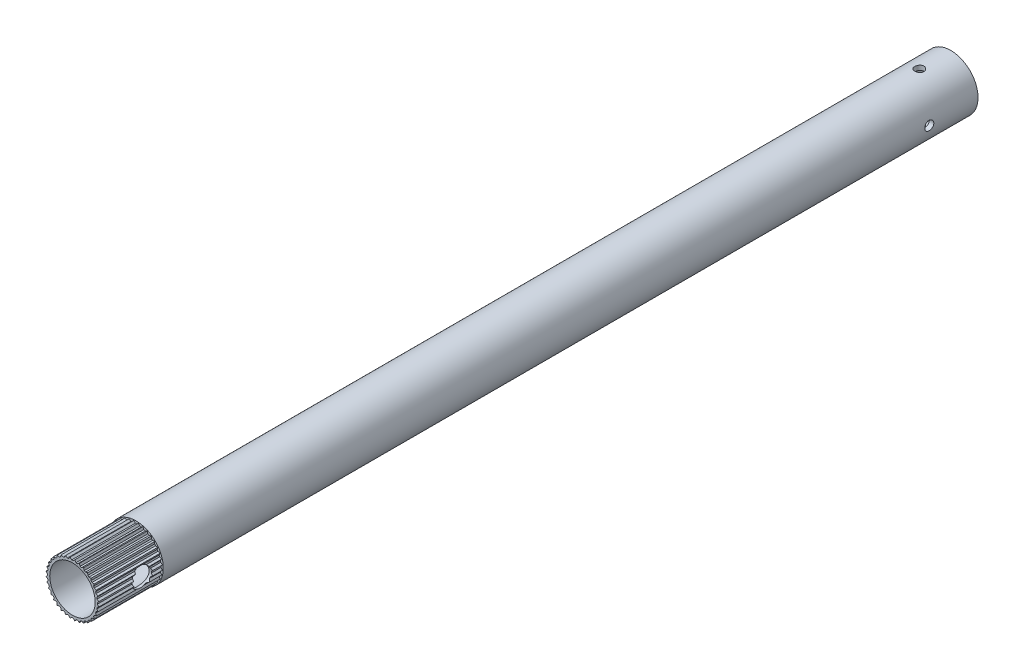
SolidWorks part; units mm, degrees
material "AISI 4130 Steel, normalized at 870C"
ref_plane "X-Y Datum" through (0, 0, 0) normal (0, 0, 1) x (1, 0, 0)
ref_plane "X-Z Datum" through (0, 0, 0) normal (0, 1, 0) x (1, 0, 0)
ref_plane "Y-Z Datum" through (0, 0, 0) normal (1, 0, 0) x (0, 0, -1)
sketch "Sketch1" plane through (0, 0, 0) normal (0, 1, 0) x (1, 0, 0)
  line L0 (9.5377, -364.395) -> (9.5377, -22.1596)
  line L1 (9.5377, -22.1596) -> (7.9375, -22.1596)
  line L2 (7.9375, -22.1596) -> (7.9375, -364.395)
  line L3 (7.9375, -364.395) -> (9.5377, -364.395)
  line L4 (0, -10.4775) -> (0, 10.4775) construction
  line L7 (0, -429.9496) -> (0, 0.9948) construction
revolve "Revolve1" [suppressed] add sketch "Sketch1" angle 360 about L7
sketch "Sketch2" plane through (0, 0, 0) normal (0, 1, 0) x (1, 0, 0)
  circle A0 centre (0, -33.1635) radius 1.5875 construction
  circle A4 centre (0, -33.1635) radius 1.5875
  circle A5 centre (0, -371.1514) radius 3.3782
  circle A6 centre (0, -371.1514) radius 3.3782 construction
extrude "Cut-Extrude2" [suppressed] cut sketch "Sketch2" against normal through all both and the other way through all
sketch "Sketch3" plane through (0, 0, 0) normal (1, 0, 0) x (0, 0, -1)
  circle A1 centre (-39.196, 0) radius 1.5875
  circle A2 centre (-39.196, 0) radius 1.5875 construction
extrude "Cut-Extrude3" [suppressed] cut sketch "Sketch3" against normal through all both and the other way through all
sketch "Sketch5" plane through (0, 0, 0) normal (0, 1, 0) x (1, 0, 0)
  line L0 (7.9375, -329.0759) -> (7.9375, -22.1596)
  line L1 (7.9375, -22.1596) -> (9.525, -22.1596)
  line L2 (9.525, -22.1596) -> (9.525, -329.0759)
  line L3 (9.525, -329.0759) -> (7.9375, -329.0759)
  line L4 (0, 0) -> (0, -348.3259) construction
  line L10 (0, 2.0157) -> (0, -439.4327) construction
revolve "Revolve2" add sketch "Sketch5" angle 360 about L10
sketch "Sketch6" plane through (0, 0, 0) normal (0, 1, 0) x (1, 0, 0)
  circle A0 centre (0, -33.1635) radius 1.5875 construction
  circle A1 centre (0, -33.1635) radius 1.5875
sketch "Sketch7" plane through (0, 0, 0) normal (1, 0, 0) x (0, 0, -1)
  circle A0 centre (-313.5823, 0) radius 3.3782 construction
  circle A2 centre (-39.196, 0) radius 1.5875
  circle A3 centre (-313.5823, 0) radius 3.3782
  circle A4 centre (-39.196, 0) radius 1.5875 construction
extrude "Cut-Extrude5" cut sketch "Sketch7" against normal through all both and the other way through all
extrude "Cut-Extrude6" cut sketch "Sketch6" against normal through all both and the other way through all
sketch "Sketch8" plane through (0, 0, 0) normal (0, 0, 1) x (1, 0, 0)
  line L0 (9.2357, -0.808) -> (8.6817, -0.254)
  line L1 (8.6817, -0.254) -> (8.6817, 0.254)
  line L2 (8.6817, 0.254) -> (9.2357, 0.808)
  line L3 (8.6817, 0) -> (0, 0) construction
  line L4 (8.9551, -2.3995) -> (8.5057, -1.7577)
  line L5 (8.5057, -1.7577) -> (8.5939, -1.2574)
  line L6 (8.5939, -1.2574) -> (9.2357, -0.808)
  line L7 (8.4024, -3.9181) -> (8.0713, -3.208)
  line L8 (8.0713, -3.208) -> (8.245, -2.7306)
  line L9 (8.245, -2.7306) -> (8.9551, -2.3995)
  line L10 (7.5944, -5.3176) -> (7.3916, -4.5608)
  line L11 (7.3916, -4.5608) -> (7.6456, -4.1209)
  line L12 (7.6456, -4.1209) -> (8.4024, -3.9181)
  line L13 (6.5556, -6.5556) -> (6.4873, -5.7751)
  line L14 (6.4873, -5.7751) -> (6.8138, -5.3859)
  line L15 (6.8138, -5.3859) -> (7.5944, -5.3176)
  line L16 (5.3176, -7.5944) -> (5.3859, -6.8138)
  line L17 (5.3859, -6.8138) -> (5.7751, -6.4873)
  line L18 (5.7751, -6.4873) -> (6.5556, -6.5556)
  line L19 (3.9181, -8.4024) -> (4.1209, -7.6456)
  line L20 (4.1209, -7.6456) -> (4.5608, -7.3916)
  line L21 (4.5608, -7.3916) -> (5.3176, -7.5944)
  line L22 (2.3995, -8.9551) -> (2.7306, -8.245)
  line L23 (2.7306, -8.245) -> (3.208, -8.0713)
  line L24 (3.208, -8.0713) -> (3.9181, -8.4024)
  line L25 (0.808, -9.2357) -> (1.2574, -8.5939)
  line L26 (1.2574, -8.5939) -> (1.7577, -8.5057)
  line L27 (1.7577, -8.5057) -> (2.3995, -8.9551)
  line L28 (-0.808, -9.2357) -> (-0.254, -8.6817)
  line L29 (-0.254, -8.6817) -> (0.254, -8.6817)
  line L30 (0.254, -8.6817) -> (0.808, -9.2357)
  line L31 (-2.3995, -8.9551) -> (-1.7577, -8.5057)
  line L32 (-1.7577, -8.5057) -> (-1.2574, -8.5939)
  line L33 (-1.2574, -8.5939) -> (-0.808, -9.2357)
  line L34 (-3.9181, -8.4024) -> (-3.208, -8.0713)
  line L35 (-3.208, -8.0713) -> (-2.7306, -8.245)
  line L36 (-2.7306, -8.245) -> (-2.3995, -8.9551)
  line L37 (-5.3176, -7.5944) -> (-4.5608, -7.3916)
  line L38 (-4.5608, -7.3916) -> (-4.1209, -7.6456)
  line L39 (-4.1209, -7.6456) -> (-3.9181, -8.4024)
  line L40 (-6.5556, -6.5556) -> (-5.7751, -6.4873)
  line L41 (-5.7751, -6.4873) -> (-5.3859, -6.8138)
  line L42 (-5.3859, -6.8138) -> (-5.3176, -7.5944)
  line L43 (-7.5944, -5.3176) -> (-6.8138, -5.3859)
  line L44 (-6.8138, -5.3859) -> (-6.4873, -5.7751)
  line L45 (-6.4873, -5.7751) -> (-6.5556, -6.5556)
  line L46 (-8.4024, -3.9181) -> (-7.6456, -4.1209)
  line L47 (-7.6456, -4.1209) -> (-7.3916, -4.5608)
  line L48 (-7.3916, -4.5608) -> (-7.5944, -5.3176)
  line L49 (-8.9551, -2.3995) -> (-8.245, -2.7306)
  line L50 (-8.245, -2.7306) -> (-8.0713, -3.208)
  line L51 (-8.0713, -3.208) -> (-8.4024, -3.9181)
  line L52 (-9.2357, -0.808) -> (-8.5939, -1.2574)
  line L53 (-8.5939, -1.2574) -> (-8.5057, -1.7577)
  line L54 (-8.5057, -1.7577) -> (-8.9551, -2.3995)
  line L55 (-9.2357, 0.808) -> (-8.6817, 0.254)
  line L56 (-8.6817, 0.254) -> (-8.6817, -0.254)
  line L57 (-8.6817, -0.254) -> (-9.2357, -0.808)
  line L58 (-8.9551, 2.3995) -> (-8.5057, 1.7577)
  line L59 (-8.5057, 1.7577) -> (-8.5939, 1.2574)
  line L60 (-8.5939, 1.2574) -> (-9.2357, 0.808)
  line L61 (-8.4024, 3.9181) -> (-8.0713, 3.208)
  line L62 (-8.0713, 3.208) -> (-8.245, 2.7306)
  line L63 (-8.245, 2.7306) -> (-8.9551, 2.3995)
  line L64 (-7.5944, 5.3176) -> (-7.3916, 4.5608)
  line L65 (-7.3916, 4.5608) -> (-7.6456, 4.1209)
  line L66 (-7.6456, 4.1209) -> (-8.4024, 3.9181)
  line L67 (-6.5556, 6.5556) -> (-6.4873, 5.7751)
  line L68 (-6.4873, 5.7751) -> (-6.8138, 5.3859)
  line L69 (-6.8138, 5.3859) -> (-7.5944, 5.3176)
  line L70 (-5.3176, 7.5944) -> (-5.3859, 6.8138)
  line L71 (-5.3859, 6.8138) -> (-5.7751, 6.4873)
  line L72 (-5.7751, 6.4873) -> (-6.5556, 6.5556)
  line L73 (-3.9181, 8.4024) -> (-4.1209, 7.6456)
  line L74 (-4.1209, 7.6456) -> (-4.5608, 7.3916)
  line L75 (-4.5608, 7.3916) -> (-5.3176, 7.5944)
  line L76 (-2.3995, 8.9551) -> (-2.7306, 8.245)
  line L77 (-2.7306, 8.245) -> (-3.208, 8.0713)
  line L78 (-3.208, 8.0713) -> (-3.9181, 8.4024)
  line L79 (-0.808, 9.2357) -> (-1.2574, 8.5939)
  line L80 (-1.2574, 8.5939) -> (-1.7577, 8.5057)
  line L81 (-1.7577, 8.5057) -> (-2.3995, 8.9551)
  line L82 (0.808, 9.2357) -> (0.254, 8.6817)
  line L83 (0.254, 8.6817) -> (-0.254, 8.6817)
  line L84 (-0.254, 8.6817) -> (-0.808, 9.2357)
  line L85 (2.3995, 8.9551) -> (1.7577, 8.5057)
  line L86 (1.7577, 8.5057) -> (1.2574, 8.5939)
  line L87 (1.2574, 8.5939) -> (0.808, 9.2357)
  line L88 (3.9181, 8.4024) -> (3.208, 8.0713)
  line L89 (3.208, 8.0713) -> (2.7306, 8.245)
  line L90 (2.7306, 8.245) -> (2.3995, 8.9551)
  line L91 (5.3176, 7.5944) -> (4.5608, 7.3916)
  line L92 (4.5608, 7.3916) -> (4.1209, 7.6456)
  line L93 (4.1209, 7.6456) -> (3.9181, 8.4024)
  line L94 (6.5556, 6.5556) -> (5.7751, 6.4873)
  line L95 (5.7751, 6.4873) -> (5.3859, 6.8138)
  line L96 (5.3859, 6.8138) -> (5.3176, 7.5944)
  line L97 (7.5944, 5.3176) -> (6.8138, 5.3859)
  line L98 (6.8138, 5.3859) -> (6.4873, 5.7751)
  line L99 (6.4873, 5.7751) -> (6.5556, 6.5556)
  line L100 (8.4024, 3.9181) -> (7.6456, 4.1209)
  line L101 (7.6456, 4.1209) -> (7.3916, 4.5608)
  line L102 (7.3916, 4.5608) -> (7.5944, 5.3176)
  line L103 (8.9551, 2.3995) -> (8.245, 2.7306)
  line L104 (8.245, 2.7306) -> (8.0713, 3.208)
  line L105 (8.0713, 3.208) -> (8.4024, 3.9181)
  line L106 (9.2357, 0.808) -> (8.5939, 1.2574)
  line L107 (8.5939, 1.2574) -> (8.5057, 1.7577)
  line L108 (8.5057, 1.7577) -> (8.9551, 2.3995)
  circle A0 centre (0, 0) radius 12.7
  circle A1 centre (0, 0) radius 9.271 construction
  circle A2 centre (0, 0) radius 8.6854 construction
  point P153 (0, 0)
  dimension "D1" = 25.4
  dimension "D4" = 18.542
  dimension "D6" = 17.3708
  dimension "D2" = 0.508
  dimension "D3" = 135
  dimension "D5" = 36
extrude "Cut-Extrude7" cut sketch "Sketch8" against normal blind 22.225 from surface at 329.0759 starting at face at (-9.525, 0, 329.0759)
